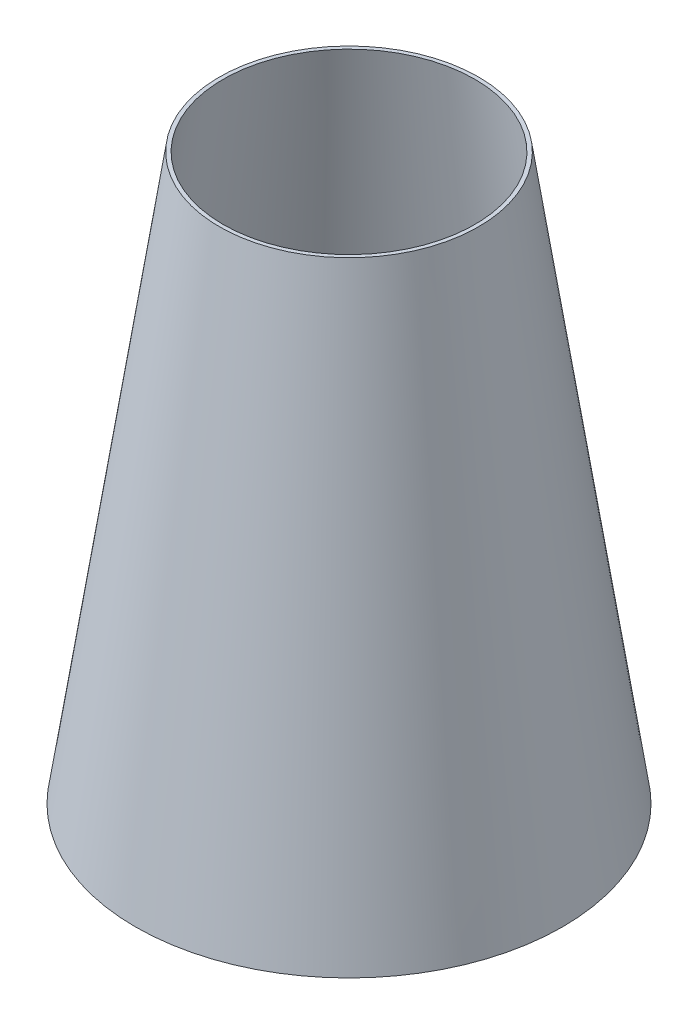
SolidWorks part; units mm, degrees
material "Hexcel AS4C (3000 Filaments)"
ref_plane "Front Plane" through (0, 0, 0) normal (0, 0, 1) x (1, 0, 0)
ref_plane "Top Plane" through (0, 0, 0) normal (0, 1, 0) x (1, 0, 0)
ref_plane "Right Plane" through (0, 0, 0) normal (1, 0, 0) x (0, 0, -1)
sketch "Sketch1" plane through (0, 0, 0) normal (0, 0, 1) x (1, 0, 0)
  line L0 (0, -74.5106) -> (0, 160.4394) construction
  line L1 (0, 160.4394) -> (-52.3875, 160.4394) construction
  line L2 (0, -74.5106) -> (-87.3125, -74.5106) construction
  line L3 (-87.3125, -74.5106) -> (-52.3875, 160.4394)
  line L4 (-52.3875, 160.4394) -> (-53.975, 160.4394)
  line L5 (-53.975, 160.4394) -> (-88.9, -74.5106)
  line L6 (-88.9, -74.5106) -> (-87.3125, -74.5106)
  dimension "D1" = 234.95
  dimension "D2" = 87.3125
  dimension "D3" = 52.3875
  dimension "D5" = 1.5875
revolve "Revolve1" add sketch "Sketch1" angle 360 about L0
